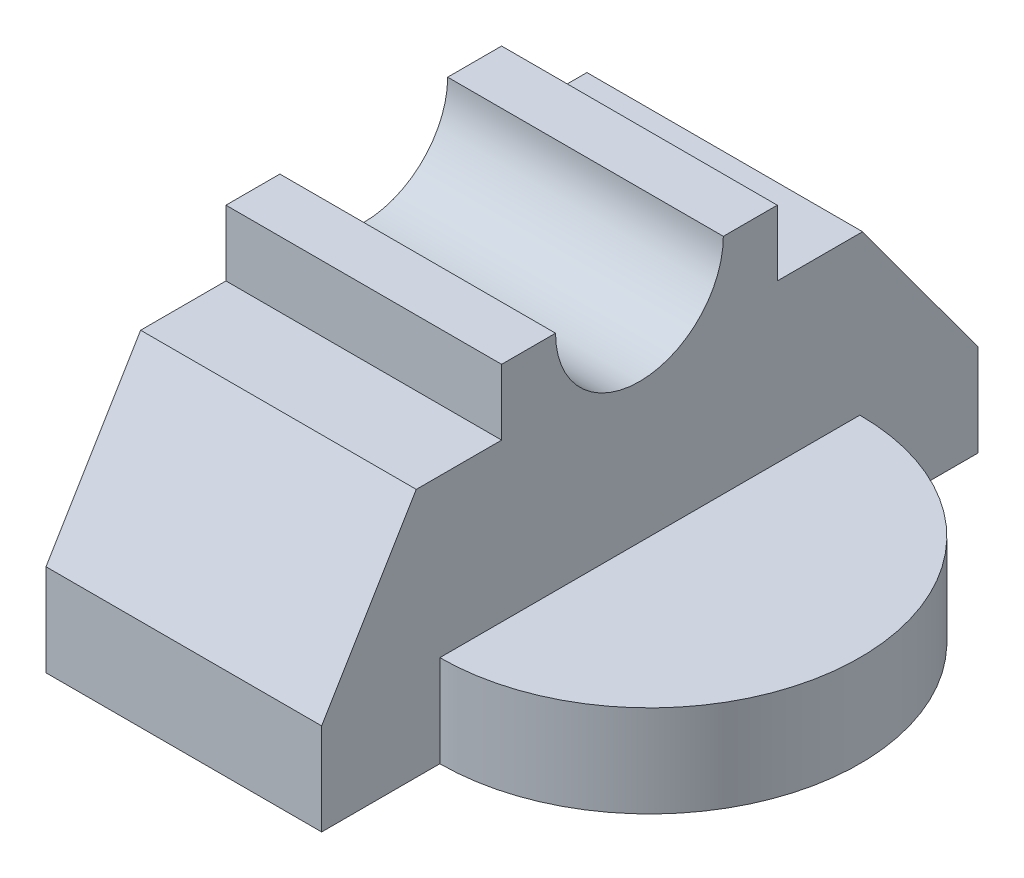
SolidWorks part; units mm, degrees
ref_plane "Front Plane" through (0, 0, 0) normal (0, 0, 1) x (1, 0, 0)
ref_plane "Top Plane" through (0, 0, 0) normal (0, 1, 0) x (1, 0, 0)
ref_plane "Right Plane" through (0, 0, 0) normal (1, 0, 0) x (0, 0, -1)
sketch "Sketch1" plane through (0, 0, 0) normal (1, 0, 0) x (0, 0, -1)
  line L0 (-45.8656, 0) -> (54.1344, 0)
  line L1 (54.1344, 0) -> (54.1344, 14)
  line L2 (54.1344, 14) -> (36.5504, 38)
  line L3 (36.5504, 38) -> (23.5504, 38)
  line L4 (23.5504, 38) -> (23.5504, 48)
  line L5 (23.5504, 48) -> (15.3333, 48)
  line L6 (-45.8656, 0) -> (-45.8656, 14)
  line L7 (-45.8656, 14) -> (-31.4496, 38)
  line L8 (-31.4496, 38) -> (-18.4496, 38)
  line L9 (-18.4496, 38) -> (-18.4496, 48)
  line L10 (-18.4496, 48) -> (-10.2326, 48)
  line L11 (-10.2326, 48) -> (15.3333, 48)
  circle A0 centre (2.5504, 48) radius 12.7829
  dimension "D1" = 100
  dimension "D2" = 14
  dimension "D3" = 14
  dimension "D4" = 38
  dimension "D5" = 38
  dimension "D6" = 48
  dimension "D8" = 68
  dimension "D9" = 42
extrude "Boss-Extrude1" add sketch "Sketch1" against normal blind 21 contours A0 L10 L9 L8 L7 L6 L0 L1 L2 L3 L4 L5
ref_plane "Plane1" through (-21, 0, 0) normal (-1, 0, 0) x (0, 0, 1)
mirror "Mirror1" about plane through (-21, 0, 0) normal (-1, 0, 0) of bodies 101
sketch "Sketch3" plane through (0, 0, 0) normal (0, -1, 0) x (1, 0, 0)
  line L0 (0, 24.2) -> (0, -20.7251)
  line L1 (0, 45.8656) -> (0, -54.1344) construction
  line L2 (0, 27.8656) -> (0, -36.1344)
  circle A0 centre (0, -4.1344) radius 32
  line M2 (0, -54.1344) -> (0, 45.8656)
extrude "Boss-Extrude2" add sketch "Sketch3" against normal blind 14 contours A0 M2
